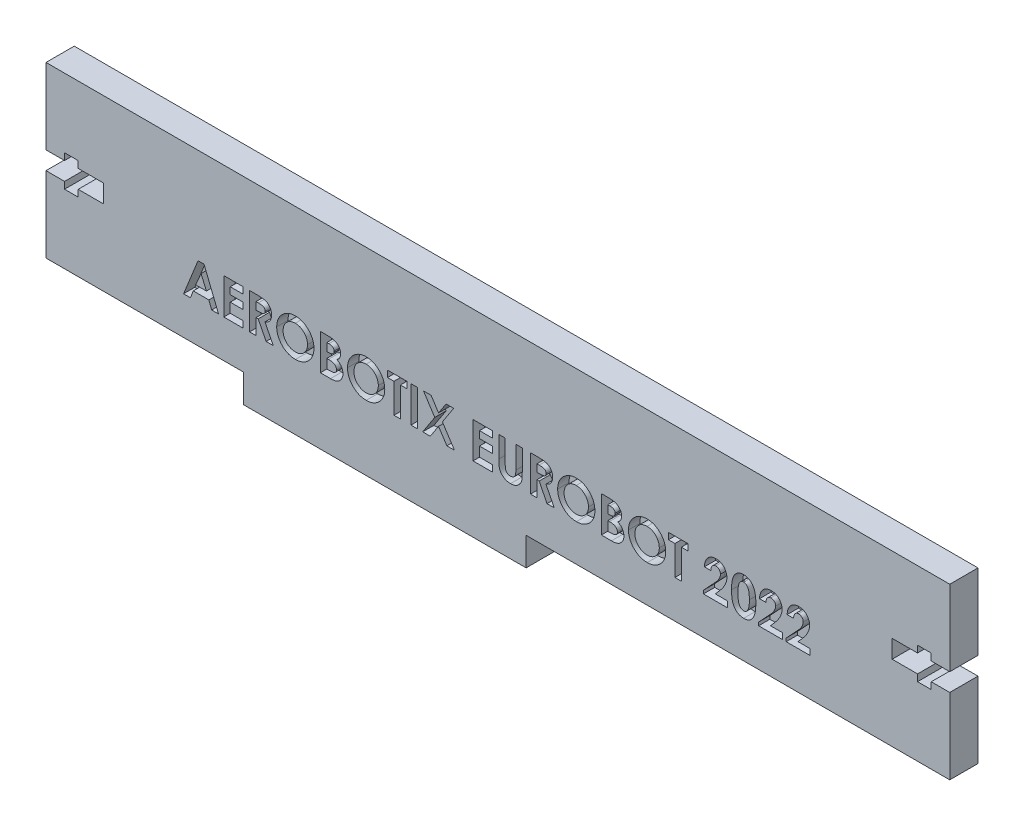
SolidWorks part; units mm, degrees
material "Acrylique (impact moyen-haut)"
ref_plane "Plan de face" through (0, 0, 0) normal (0, 0, 1) x (1, 0, 0)
ref_plane "Plan de dessus" through (0, 0, 0) normal (0, 1, 0) x (1, 0, 0)
ref_plane "Plan de droite" through (0, 0, 0) normal (1, 0, 0) x (0, 0, -1)
sketch "Esquisse1" plane through (0, 0, 0) normal (0, 0, 1) x (1, 0, 0)
  line L0 (-54.1382, -12.4074) -> (-54.1382, -17.4074)
  line L1 (70.8618, -12.4074) -> (-4.1382, -12.4074)
  line L2 (70.8618, -12.4074) -> (70.8618, 1.0033)
  line L3 (70.8618, 17.5926) -> (-89.1382, 17.5926)
  line L4 (-89.1382, -12.4074) -> (-89.1382, 1.0033)
  line L5 (-54.1382, -17.4074) -> (-4.1382, -17.4074)
  line L6 (-4.1382, -17.4074) -> (-4.1382, -12.4074)
  line L7 (-54.1382, -12.4074) -> (-89.1382, -12.4074)
  line L8 (-85.8563, 4.1926) -> (-89.1382, 4.1801)
  line L9 (-85.8563, 4.1926) -> (-85.8563, 5.3926)
  line L10 (-85.8563, 5.3926) -> (-83.4363, 5.3926)
  line L11 (-83.4363, 5.3926) -> (-83.4363, 4.1926)
  line L12 (-83.4363, 4.1926) -> (-78.9382, 4.1926)
  line L13 (-78.9382, 4.1926) -> (-78.9382, 0.9926)
  line L14 (-78.9382, 0.9926) -> (-83.4363, 0.9926)
  line L15 (-83.4363, 0.9926) -> (-83.4363, -0.2074)
  line L16 (-83.4363, -0.2074) -> (-85.8563, -0.2074)
  line L17 (-85.8563, -0.2074) -> (-85.8563, 0.9926)
  line L18 (-85.8563, 0.9926) -> (-89.1382, 1.0033)
  line L19 (-94.1382, 1.0033) -> (-89.1382, 1.0033) construction
  line L20 (-89.1382, 4.1801) -> (-89.1382, 17.5926)
  line L21 (-9.1382, 17.5926) -> (-9.1382, -12.4074) construction
  line L22 (-99.3382, -12.4074) -> (340.6618, -12.4074) construction
  line L23 (67.58, 0.9926) -> (70.8618, 1.0033)
  line L24 (67.58, -0.2074) -> (67.58, 0.9926)
  line L25 (65.16, -0.2074) -> (67.58, -0.2074)
  line L26 (65.16, 0.9926) -> (65.16, -0.2074)
  line L27 (60.6618, 0.9926) -> (65.16, 0.9926)
  line L28 (60.6618, 4.1926) -> (60.6618, 0.9926)
  line L29 (65.16, 4.1926) -> (60.6618, 4.1926)
  line L30 (65.16, 5.3926) -> (65.16, 4.1926)
  line L31 (67.58, 5.3926) -> (65.16, 5.3926)
  line L32 (67.58, 4.1926) -> (67.58, 5.3926)
  line L33 (67.58, 4.1926) -> (70.8618, 4.1801)
  line L34 (70.8618, 4.1801) -> (70.8618, 17.5926)
  dimension "D1" = 160
  dimension "D2" = 30
  dimension "D3" = 50
  dimension "D4" = 5
  dimension "D5" = 35
extrude "Boss.-Extru.1" add sketch "Esquisse1" along normal blind 5
sketch "Esquisse2" plane through (0, 0, 5) normal (0, 0, 1) x (1, 0, 0)
  line L0 (-89.1382, -5.702) -> (70.8618, -5.702) construction
  line L1 (-89.1382, 1.0033) -> (-89.1382, -12.4074) construction
  line L2 (70.8618, -12.4074) -> (70.8618, 1.0033) construction
  text T0 "AEROBOTIX EUROBOT 2022" font "Century Gothic" height in points 24
extrude "Enlèv. mat.-Extru.1" cut sketch "Esquisse2" against normal blind 2
sketch "Esquisse3" plane through (0, 0, 0) normal (0, 0, -1) x (-1, 0, 0)
  line L0 (-70.8618, -5.702) -> (89.1382, -5.702) construction
  line L1 (-70.8618, -12.4074) -> (-70.8618, 1.0033) construction
  line L2 (89.1382, 1.0033) -> (89.1382, -12.4074) construction
  text T0 "<b>EUROBOT 2022 WINNERS</b>" font "Century Gothic" height in points 28
extrude "Enlèv. mat.-Extru.2" cut sketch "Esquisse3" against normal blind 1
